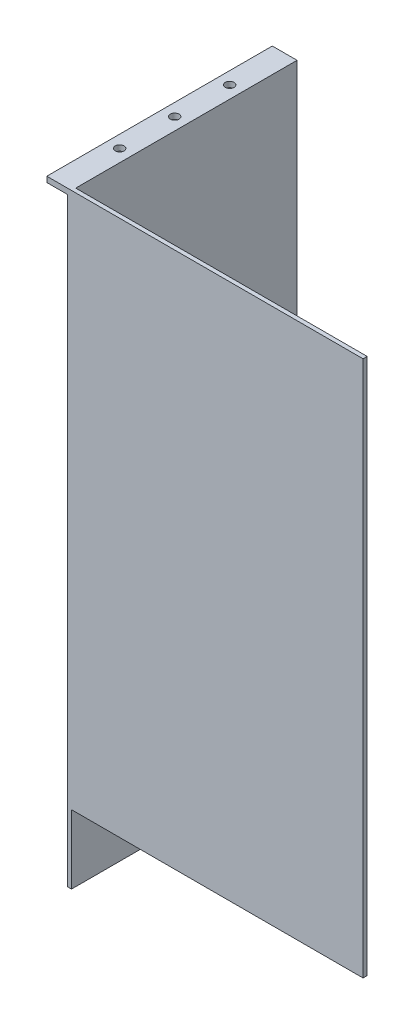
SolidWorks part; units mm, degrees
ref_plane "前视基准面" through (0, 0, 0) normal (0, 0, 1) x (1, 0, 0)
ref_plane "上视基准面" through (0, 0, 0) normal (0, 1, 0) x (1, 0, 0)
ref_plane "右视基准面" through (0, 0, 0) normal (1, 0, 0) x (0, 0, -1)
sketch "草图1" plane through (0, 0, 0) normal (0, 0, 1) x (1, 0, 0)
  line L1 (0, 0) -> (106, 0)
  line L2 (0, 0) -> (0, -195)
  line L3 (0, -195) -> (106, -195)
  line L4 (106, 0) -> (106, -195)
extrude "凸台-拉伸1" add sketch "草图1" along normal blind 1.5
ref_plane "基准面4" through (0, 0, 0) normal (-1, 0, 0) x (0, 0, 1)
sketch "草图2" plane through (0, 0, 0) normal (-1, 0, 0) x (0, 0, 1)
  line L1 (1.5, -220) -> (-80.5, -220)
  line L2 (1.5, -220) -> (1.5, 0)
  line L3 (1.5, 0) -> (-80.5, 0)
  line L4 (-80.5, -220) -> (-80.5, 0)
  point P0 (1.5, -220)
  dimension "D1" = 25
extrude "凸台-拉伸2" add sketch "草图2" along normal blind 1.5
sketch "草图3" plane through (0, 0, 0) normal (-1, 0, 0) x (0, 0, 1)
  line L0 (1.5, -220) -> (1.5, 0) construction
  line L1 (-80.5, 0) -> (1.5, 0)
  line L2 (-80.5, 0) -> (-80.5, -2)
  line L3 (-80.5, -2) -> (1.5, -2)
  line L4 (1.5, 0) -> (1.5, -2)
extrude "凸台-拉伸3" add sketch "草图3" along normal blind 9
sketch "草图5" plane through (0, 0, 0) normal (0, 1, 0) x (1, 0, 0)
  line L0 (-9, -1.5) -> (-9, 80.5) construction
  circle A0 centre (-4.5, 60.5) radius 1.6
  circle A1 centre (-4.5, 40.5) radius 1.6
  circle A2 centre (-4.5, 20.5) radius 1.6
  point P0 (-9, 60.5)
  point P1 (-9, 40.5)
  point P4 (-9, 20.5)
  point P6 (-4.5, 60.5)
  point P7 (-4.5, 40.5)
  point P8 (-4.5, 20.5)
  dimension "D4" = 3.2
  dimension "D1" = 20
  dimension "D2" = 20
  dimension "D3" = 20
extrude "切除-拉伸1" cut sketch "草图5" against normal blind 9
